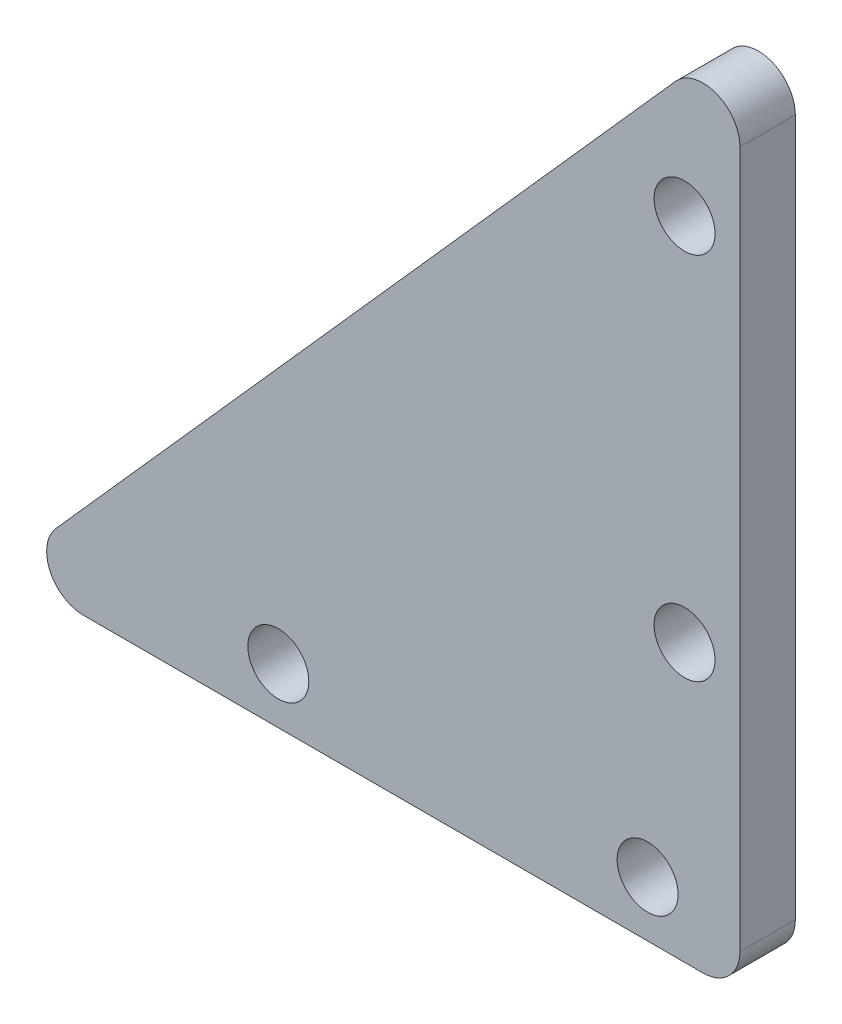
SolidWorks part; units mm, degrees
material "玻纤板"
ref_plane "前视基准面" through (0, 0, 0) normal (0, 0, 1) x (1, 0, 0)
ref_plane "上视基准面" through (0, 0, 0) normal (0, 1, 0) x (1, 0, 0)
ref_plane "右视基准面" through (0, 0, 0) normal (1, 0, 0) x (0, 0, -1)
other "Configuration Table"
sketch "草图1" plane through (0, 0, 0) normal (0, 0, 1) x (1, 0, 0)
  line L0 (0, 0) -> (-40, 0)
  line L1 (-40, 0) -> (0, 45)
  line L2 (0, 45) -> (0, 0)
  dimension "D1" = 45
  dimension "D2" = 40
extrude "凸台-拉伸1" add sketch "草图1" along normal blind 3
sketch "草图2" plane through (0, 0, 3) normal (0, 0, 1) x (1, 0, 0)
  line L0 (0, 0) -> (0, 45) construction
  line L1 (-40, 0) -> (0, 0) construction
  circle A0 centre (-5, 3) radius 1.65
  circle A1 centre (-25, 3) radius 1.65
  dimension "D1" = 5
  dimension "D2" = 3
  dimension "D3" = 3.3
  dimension "D4" = 20
extrude "切除-拉伸1" cut sketch "草图2" against normal blind 3
sketch "草图3" plane through (0, 0, 3) normal (0, 0, 1) x (1, 0, 0)
  line L0 (-40, 0) -> (0, 0) construction
  line L1 (0, 0) -> (0, 45) construction
  circle A0 centre (-3, 15) radius 1.65
  circle A1 centre (-3, 35) radius 1.65
  dimension "D1" = 15
  dimension "D3" = 20
  dimension "D4" = 3.3
  dimension "D2" = 3
extrude "切除-拉伸2" cut sketch "草图3" against normal blind 3
fillet "圆角1" radius 2 3 edges at (0, 0, 1.5) (-40, 0, 1.5) (0, 45, 1.5)
